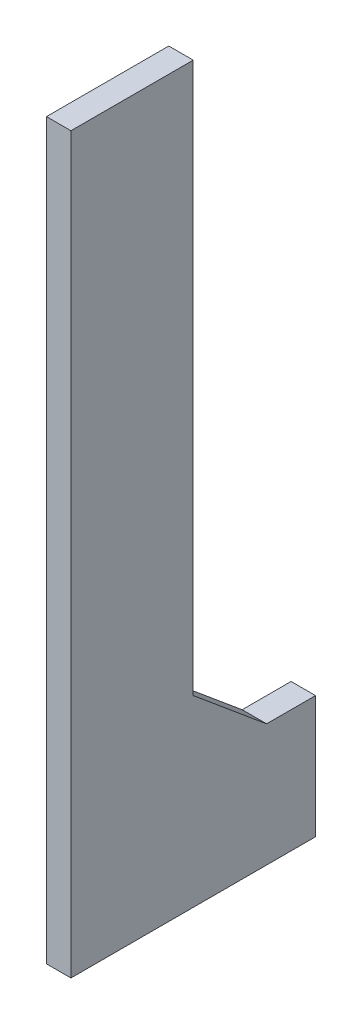
SolidWorks part; units mm, degrees
ref_plane "Спереди" through (0, 0, 0) normal (0, 0, 1) x (1, 0, 0)
ref_plane "Сверху" through (0, 0, 0) normal (0, 1, 0) x (1, 0, 0)
ref_plane "Справа" through (0, 0, 0) normal (1, 0, 0) x (0, 0, -1)
sketch "Эскиз1" plane through (0, 0, 0) normal (1, 0, 0) x (0, 0, -1)
  line L0 (0, 0) -> (100, 0)
  line L1 (100, 0) -> (100, 50)
  line L2 (100, 50) -> (80, 50)
  line L3 (80, 50) -> (50, 75)
  line L4 (50, 75) -> (50, 300)
  line L5 (50, 300) -> (0, 300)
  line L6 (0, 300) -> (0, 0)
  point P3 (50, 74.2229)
  point P9 (34.4673, 24.6818)
  point P10 (21.2441, 54.3847)
  point P11 (-29.4889, 0)
  point P12 (-1.8746, 0)
  point P13 (70.0602, 50)
  dimension "D1" = 100
  dimension "D2" = 50
  dimension "D3" = 50
  dimension "D4" = 300
  dimension "D5" = 20
  dimension "D6" = 25
extrude "Боковая панель" add sketch "Эскиз1" along normal blind 10
